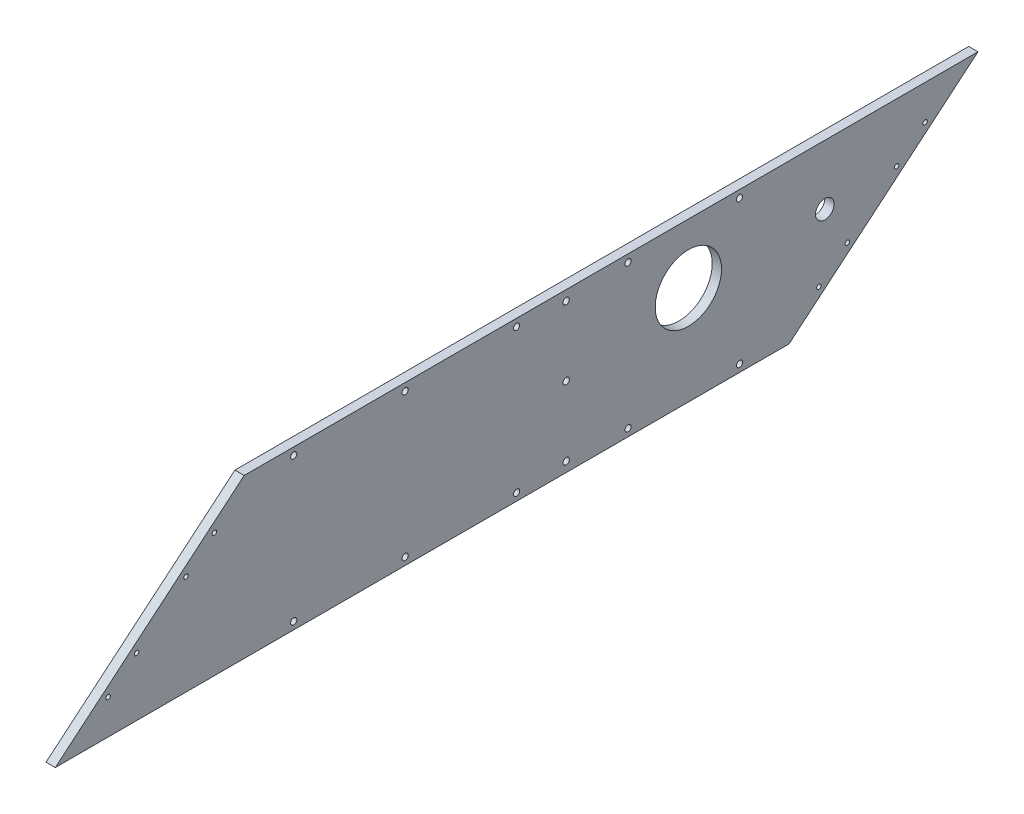
SolidWorks part; units mm, degrees
material "6061-T6 (SS)"
ref_plane "Front Plane" through (0, 0, 0) normal (0, 0, 1) x (1, 0, 0)
ref_plane "Top Plane" through (0, 0, 0) normal (0, 1, 0) x (1, 0, 0)
ref_plane "Right Plane" through (0, 0, 0) normal (1, 0, 0) x (0, 0, -1)
sketch "Sketch1" plane through (0, 0, 0) normal (1, 0, 0) x (0, 0, -1)
  line L0 (0, 12.7) -> (0, -12.7) construction
  line L1 (0, -12.7) -> (33.2976, -40.64) construction
  line L2 (33.2976, -40.64) -> (312.6976, -40.64)
  line L3 (312.6976, -40.64) -> (345.9952, -12.7)
  line L4 (345.9952, -12.7) -> (345.9952, 12.7) construction
  line L5 (345.9952, 12.7) -> (312.6976, 40.64) construction
  line L6 (312.6976, 40.64) -> (33.2976, 40.64)
  line L7 (33.2976, 40.64) -> (0, 12.7)
  line L8 (33.2976, 40.64) -> (33.2976, -40.64) construction
  line L9 (312.6976, 40.64) -> (312.6976, -40.64) construction
  line L10 (0, 0) -> (345.9952, 0) construction
  line L11 (0, 12.7) -> (-63.5681, -40.64)
  line L12 (-63.5681, -40.64) -> (33.2976, -40.64)
  line L13 (312.6976, 40.64) -> (409.5633, 40.64)
  line L14 (409.5633, 40.64) -> (345.9952, -12.7)
  point P10 (33.2976, 0)
  point P12 (312.6976, 0)
  dimension "D1" = 81.28
  dimension "D2" = 279.4
  dimension "D3" = 25.4
  dimension "D4" = 40
extrude "Boss-Extrude1" add sketch "Sketch1" along normal blind 4.7625
sketch "Sketch2" plane through (4.7625, 0, 0) normal (1, 0, 0) x (0, 0, -1)
  line L0 (-3.2177, 10) -> (373.048, 10) construction
  line L1 (312.6976, -40.64) -> (409.5633, 40.64) construction
  line L2 (345.048, 10) -> (245.048, 10) construction
  line L3 (245.048, -5) -> (345.048, -5) construction
  line L4 (245.048, -5) -> (245.048, 25) construction
  line L5 (245.048, 25) -> (345.048, 25) construction
  line L6 (345.048, -5) -> (345.048, 25) construction
  line L7 (33.2976, 40.64) -> (-63.5681, -40.64) construction
  line L9 (0, 0) -> (361.1305, 0) construction
  circle A0 centre (300.048, 10) radius 6.9977 construction
  circle A1 centre (282.2147, 8) radius 1.4986 construction
  circle A2 centre (270.2178, 15.9334) radius 0.9906 construction
  circle A3 centre (282.2147, 8) radius 11.4777 construction
  circle A4 centre (270.2178, 15.9334) radius 7.1501 construction
  circle A5 centre (300.048, 10) radius 12.827 construction
  circle A6 centre (261.048, 10) radius 17
  circle A7 centre (282.2147, 8) radius 5.1181 construction
  circle A8 centre (331.0042, 10) radius 4.7625
  point P11 (300.048, 10)
  point P12 (282.2147, 8)
  point P13 (270.2178, 15.9334)
  point P23 (261.048, 10)
  dimension "D5" = 13.9954
  dimension "D6" = 2.9972
  dimension "D7" = 1.9812
  dimension "D8" = 25.654
  dimension "D9" = 22.9553
  dimension "D10" = 14.3002
  dimension "D12" = 34
  dimension "D13" = 10.2362
  dimension "D17" = 9.525
  dimension "D1" = 17.9451
  dimension "D2" = 14.3828
  dimension "D3" = 30
  dimension "D4" = 100
  dimension "D11" = 10.922
  dimension "D14" = 16
  dimension "D15" = 13
  dimension "D16" = 55
  dimension "D18" = 30.9562
  dimension "D19" = 28
  dimension "D20" = 10
extrude "Gearbox (with Press fits)" cut sketch "Sketch2" against normal through all
sketch "Sketch3" plane through (4.7625, 0, 0) normal (1, 0, 0) x (0, 0, -1)
  line L0 (0, 0) -> (361.1305, 0) construction
  line L1 (28.757, 36.83) -> (405.0227, 36.83) construction
  line L2 (33.2976, 40.64) -> (-63.5681, -40.64) construction
  line L5 (409.5633, 40.64) -> (33.2976, 40.64) construction
  line L6 (312.6976, -40.64) -> (409.5633, 40.64) construction
  circle A0 centre (287.2976, 36.83) radius 1.5811
  circle A1 centre (230.1476, 36.83) radius 1.5811
  circle A2 centre (172.9976, 36.83) radius 1.5811
  circle A3 centre (115.8476, 36.83) radius 1.5811
  circle A4 centre (58.6976, 36.83) radius 1.5812
  circle A5 centre (58.6976, -36.83) radius 1.5812
  circle A6 centre (115.8476, -36.83) radius 1.5811
  circle A7 centre (172.9976, -36.83) radius 1.5811
  circle A8 centre (230.1476, -36.83) radius 1.5811
  circle A9 centre (287.2976, -36.83) radius 1.5811
  dimension "D1" = 3.1623
  dimension "D2" = 25.4
  dimension "D3" = 3.81
  dimension "D4" = 5
extrude "Cut-Extrude1" cut sketch "Sketch3" against normal through all
hole_wizard "#2 Clearance Hole1" positions "Sketch6" profile "Sketch5" hole size "#2" standard "ANSI Inch"
sketch "Sketch6" plane through (4.7625, 0, 0) normal (1, 0, 0) x (0, 0, -1)
  line L0 (241.1305, 40.64) -> (241.1305, -40.64) construction
  line L1 (409.5633, 40.64) -> (33.2976, 40.64) construction
  line L2 (-63.5681, -40.64) -> (312.6976, -40.64) construction
  line L4 (244.1305, 40.64) -> (244.1305, -40.64) construction
  line L6 (241.1305, -16) -> (342.0624, -16) construction
  line L7 (312.6976, -40.64) -> (409.5633, 40.64) construction
  line L9 (241.1305, -13) -> (345.6377, -13) construction
  line L11 (241.1305, 13) -> (376.6233, 13) construction
  line L12 (308.1305, 13) -> (308.1305, -13) construction
  circle A0 centre (257.1305, 0) radius 14 construction
  point P28 (267.1305, -13)
  point P30 (308.1305, -13)
  point P32 (244.1305, -13)
  point P34 (244.1305, 13)
  point P36 (275.1305, 13)
  point P38 (308.1305, 13)
  dimension "D1" = 3
  dimension "D2" = 3
  dimension "D3" = 26
  dimension "D4" = 29
  dimension "D5" = 16
  dimension "D6" = 16
  dimension "D7" = 67
  dimension "D8" = 34
sketch "Sketch5" plane through (4.7625, -13, -267.1305) normal (0, 1, 0) x (0, 0, -1)
  line L0 (0, 0) -> (0, 5.5586)
  line L1 (0, 5.5586) -> (1.2192, 4.826)
  line L2 (1.2192, 4.826) -> (1.2192, 0)
  line L5 (1.2192, 0) -> (0, 0)
  line L10 (0, 5.5586) -> (-1.2192, 4.826) construction
  line L11 (0, -6.35) -> (0, 107.95) construction
  dimension "Hole Dia." = 2.4384
  dimension "Hole Depth" = 4.826
  dimension "Drill Angle" = 118
hole_wizard "#4-40 Tapped Hole1" positions "Sketch8" profile "Sketch9" tap size "#4-40" standard "ANSI Inch" end condition through all
sketch "Sketch8" plane through (4.7625, 0, 0) normal (1, 0, 0) x (0, 0, -1)
  line L0 (-15.1353, 0) -> (361.1305, 0) construction
  line L1 (33.2976, 40.64) -> (-63.5681, -40.64) construction
  line L2 (312.6976, -40.64) -> (409.5633, 40.64) construction
  line L4 (403.636, 40.64) -> (306.7703, -40.64) construction
  line L5 (409.5633, 40.64) -> (33.2976, 40.64) construction
  line L6 (-63.5681, -40.64) -> (312.6976, -40.64) construction
  line L8 (39.2249, 40.64) -> (-57.6408, -40.64) construction
  line L10 (355.2032, 0) -> (-9.208, 0) construction
  line L11 (327.9626, -22.8575) -> (-36.4485, -22.8575) construction
  line L13 (342.5558, -10.6124) -> (-21.8554, -10.6124) construction
  line L15 (3.4394, 10.6124) -> (367.8505, 10.6124) construction
  line L17 (18.0326, 22.8575) -> (382.4437, 22.8575) construction
  point P25 (327.9626, -22.8575)
  point P27 (342.5558, -10.6124)
  point P29 (367.8505, 10.6124)
  point P31 (382.4437, 22.8575)
  point P34 (-36.4485, -22.8575)
  point P36 (-21.8554, -10.6124)
  point P38 (3.4394, 10.6124)
  point P40 (18.0326, 22.8575)
  dimension "D1" = 16.51
  dimension "D2" = 19.05
  dimension "D3" = 16.51
  dimension "D4" = 19.05
  dimension "D5" = 3.81
  dimension "D6" = 3.81
sketch "Sketch9" plane through (4.7625, -22.8575, -327.9626) normal (0, 1, 0) x (0, 0, -1)
  line L0 (0, 0) -> (0, 4.7625)
  line L1 (0, 4.7625) -> (1.1303, 4.7625)
  line L2 (1.1303, 4.7625) -> (1.1303, 0)
  line L5 (1.1303, 0) -> (0, 0)
  line L11 (0, -6.35) -> (0, 107.95) construction
  dimension "Thru Tap Drill Dia." = 2.2606
  dimension "Thru Tap Drill Depth" = 4.7625
cosmetic thread "Hole Thread1" parameters "D2"=2.8448
cosmetic thread "Hole Thread2" parameters "D2"=2.8448
cosmetic thread "Hole Thread3" parameters "D2"=2.8448
cosmetic thread "Hole Thread4" parameters "D2"=2.8448
cosmetic thread "Hole Thread5" parameters "D2"=2.8448
cosmetic thread "Hole Thread6" parameters "D2"=2.8448
cosmetic thread "Hole Thread7" parameters "D2"=2.8448
cosmetic thread "Hole Thread8" parameters "D2"=2.8448
hole_wizard "#4 Clearance Hole1" positions "Sketch11" profile "Sketch10" hole size "#4" standard "ANSI Inch"
sketch "Sketch11" plane through (4.7625, 0, 0) normal (1, 0, 0) x (0, 0, -1)
  line L0 (27.2435, 35.56) -> (403.5092, 35.56) construction
  line L1 (33.2976, 40.64) -> (-63.5681, -40.64) construction
  line L2 (312.6976, -40.64) -> (409.5633, 40.64) construction
  line L4 (-15.1353, 0) -> (361.1305, 0) construction
  line L5 (198.3976, 35.56) -> (198.3976, -35.56) construction
  line L6 (409.5633, 40.64) -> (33.2976, 40.64) construction
  point P12 (198.3976, 35.56)
  point P15 (198.3976, -35.56)
  point P20 (198.3976, 0)
  dimension "D1" = 5.08
  dimension "D2" = 165.1
sketch "Sketch10" plane through (4.7625, 35.56, -198.3976) normal (0, 1, 0) x (0, 0, -1)
  line L0 (0, 0) -> (0, 5.8066)
  line L1 (0, 5.8066) -> (1.6319, 4.826)
  line L2 (1.6319, 4.826) -> (1.6319, 0)
  line L5 (1.6319, 0) -> (0, 0)
  line L10 (0, 5.8066) -> (-1.6319, 4.826) construction
  line L11 (0, -6.35) -> (0, 107.95) construction
  dimension "Hole Dia." = 3.2639
  dimension "Hole Depth" = 4.826
  dimension "Drill Angle" = 118
